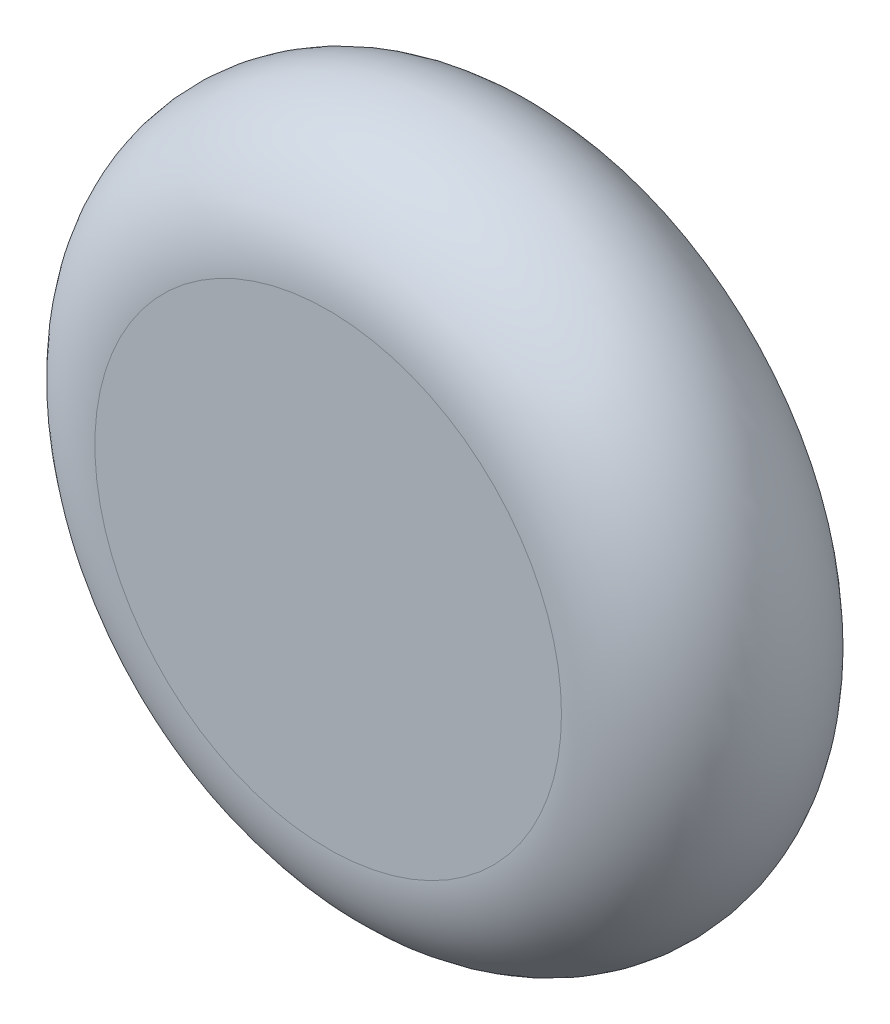
SolidWorks part; units mm, degrees
material "Custom Plastic"
ref_plane "Front Plane" through (0, 0, 0) normal (0, 0, 1) x (1, 0, 0)
ref_plane "Top Plane" through (0, 0, 0) normal (0, 1, 0) x (1, 0, 0)
ref_plane "Right Plane" through (0, 0, 0) normal (1, 0, 0) x (0, 0, -1)
sketch "Sketch2" plane through (0, 0, 0) normal (1, 0, 0) x (0, 0, -1)
  line L0 (0, 0) -> (0, 135)
  line L1 (0, 135) -> (-45, 135)
  line L2 (-45, 135) -> (-45, 0)
  line L3 (-45, 0) -> (0, 0)
  line L4 (0, 0) -> (35, 0)
  line L5 (35, 0) -> (35, 135)
  line L6 (35, 135) -> (0, 135)
  circle A0 centre (0, 90) radius 45
  dimension "D2" = 135
  dimension "D1" = 45
  dimension "D3" = 80
revolve "Revolve1" add sketch "Sketch2" angle 360 about L3
sketch "Sketch3" plane through (0, 0, -35) normal (0, 0, -1) x (-1, 0, 0)
  circle A0 centre (0, 0) radius 7.5
  dimension "D1" = 15
extrude "Boss-Extrude1" add sketch "Sketch3" along normal blind 20
